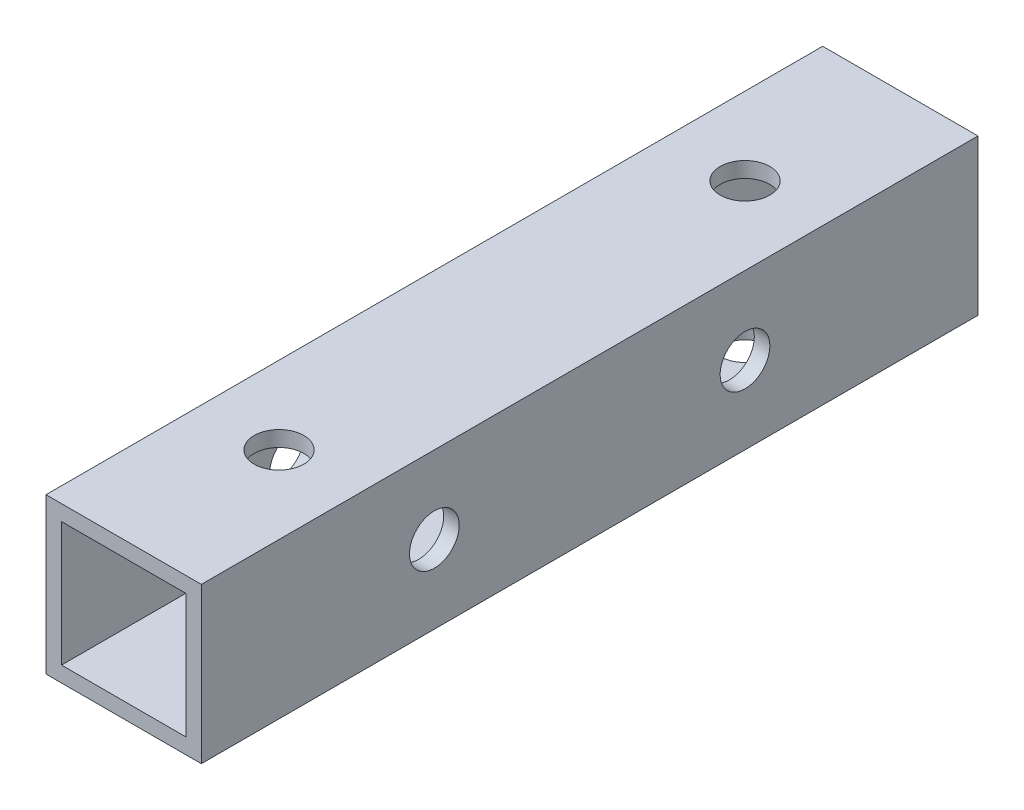
SolidWorks part; units mm, degrees
material "6061 合金"
ref_plane "正面" through (0, 0, 0) normal (0, 0, 1) x (1, 0, 0)
ref_plane "平面" through (0, 0, 0) normal (0, 1, 0) x (1, 0, 0)
ref_plane "右側面" through (0, 0, 0) normal (1, 0, 0) x (0, 0, -1)
sketch "断面 スケッチ" plane through (0, 0, 0) normal (0, 0, 1) x (1, 0, 0)
  line L1 (-5, -5) -> (5, -5)
  line L2 (-5, -5) -> (-5, 5)
  line L3 (-5, 5) -> (5, 5)
  line L4 (5, -5) -> (5, 5)
  line L5 (-5, -5) -> (5, 5) construction
  line L6 (-5, 5) -> (5, -5) construction
  point P0 (0, 0)
  dimension "D1" = 10
extrude "フレーム全長" add sketch "断面 スケッチ" along normal blind 50 thin thin type one direction reverse wall 1
sketch "上面穴 スケッチ" plane through (0, 5, 0) normal (0, 1, 0) x (1, 0, 0)
  line L0 (0, 0) -> (0, -50) construction
  line L1 (5, 0) -> (-5, 0) construction
  line L2 (5, -50) -> (-5, -50) construction
  line L3 (-5, -25) -> (5, -25) construction
  line L4 (-5, -50) -> (-5, 0) construction
  line L5 (5, -50) -> (5, 0) construction
  circle A0 centre (0, -10) radius 1.6
  circle A1 centre (0, -40) radius 1.6
  dimension "D1" = 10
  dimension "D2" = 3.2
  dimension "D3" = 10
sketch "側面穴 スケッチ" plane through (5, 0, 0) normal (1, 0, 0) x (0, 0, -1)
  line L0 (0, 0) -> (-50, 0) construction
  line L1 (0, -5) -> (0, 5) construction
  line L2 (-50, -5) -> (-50, 5) construction
  line L3 (-25, 5) -> (-25, -5) construction
  line L4 (-50, 5) -> (0, 5) construction
  line L5 (-50, -5) -> (0, -5) construction
  circle A0 centre (-15, 0) radius 1.6
  circle A1 centre (-35, 0) radius 1.6
  dimension "D1" = 15
  dimension "D2" = 3.2
  dimension "D3" = 3.2
  dimension "D4" = 15
extrude "上面穴貫通" cut sketch "上面穴 スケッチ" against normal through all
extrude "側面穴貫通" cut sketch "側面穴 スケッチ" against normal through all
fillet "フィレット" [suppressed] radius 5
